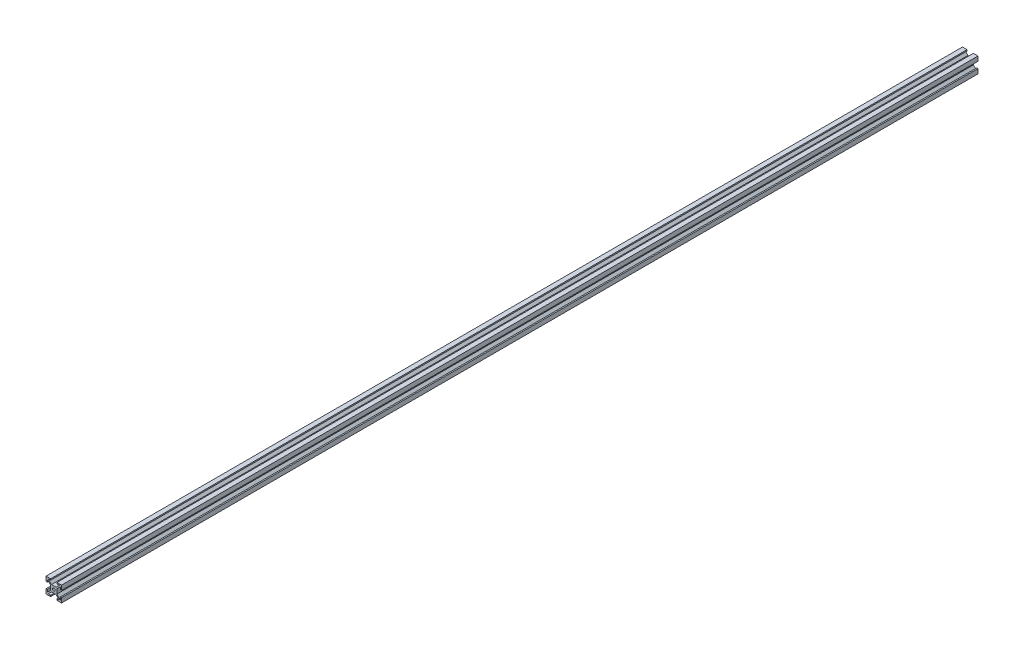
SolidWorks part; units mm, degrees
ref_plane "Front Plane" through (0, 0, 0) normal (0, 0, 1) x (1, 0, 0)
ref_plane "Top Plane" through (0, 0, 0) normal (0, 1, 0) x (1, 0, 0)
ref_plane "Right Plane" through (0, 0, 0) normal (1, 0, 0) x (0, 0, -1)
sketch "Sketch1" plane through (0, 0, 0) normal (0, 0, 1) x (1, 0, 0)
  line L0 (-8.38, 4.1) -> (-10, 4.1)
  line L1 (-2.9545, 4.1) -> (2.9545, 4.1)
  line L2 (-4.1, 2.9545) -> (-4.1, -2.9545)
  line L3 (-2.9545, -4.1) -> (2.9545, -4.1)
  line L4 (4.1, 2.9545) -> (4.1, -2.9545)
  line L5 (-4.1, 4.1) -> (4.1, -4.1) construction
  line L6 (-4.1, -4.1) -> (4.1, 4.1) construction
  line L7 (-10, 10) -> (-4.1, 10)
  line L8 (-10, 10) -> (-10, 4.1)
  line L9 (-10, -10) -> (-4.1, -10)
  line L10 (10, 10) -> (10, 4.1)
  line L11 (-10, 10) -> (10, -10) construction
  line L12 (-10, -10) -> (10, 10) construction
  line L13 (-7.2345, 8.38) -> (-4.1, 8.38)
  line L14 (-8.38, 7.2345) -> (-8.38, 4.1)
  line L15 (-7.2345, -8.38) -> (-4.1, -8.38)
  line L16 (8.38, 7.2345) -> (8.38, 4.1)
  line L17 (-8.38, 8.38) -> (8.38, -8.38) construction
  line L18 (-8.38, -8.38) -> (8.38, 8.38) construction
  line L19 (-4.1, 8.38) -> (-4.1, 10)
  line L20 (4.1, 10) -> (4.1, 8.38)
  line L21 (8.38, 4.1) -> (10, 4.1)
  line L22 (-8.38, -4.1) -> (-10, -4.1)
  line L23 (-4.1, -8.38) -> (-4.1, -10)
  line L24 (8.38, -4.1) -> (10, -4.1)
  line L25 (4.1, -8.38) -> (4.1, -10)
  line L26 (-5.464, 5.464) -> (-4.8912, 6.0368) construction
  line L27 (-4.1, 2.9545) -> (-8.38, 7.2345)
  line L28 (-2.9545, 4.1) -> (-7.2345, 8.38)
  line L29 (0, 11.3108) -> (0, -17.1823) construction
  line L30 (-16.7028, 0) -> (14.4032, 0) construction
  line L31 (-2.9545, -4.1) -> (-7.2345, -8.38)
  line L32 (-4.1, -2.9545) -> (-8.38, -7.2345)
  line L33 (2.9545, -4.1) -> (7.2345, -8.38)
  line L34 (4.1, -2.9545) -> (8.38, -7.2345)
  line L35 (4.1, 2.9545) -> (8.38, 7.2345)
  line L36 (2.9545, 4.1) -> (7.2345, 8.38)
  line L37 (4.1, 8.38) -> (7.2345, 8.38)
  line L38 (4.1, 10) -> (10, 10)
  line L39 (-8.38, -4.1) -> (-8.38, -7.2345)
  line L40 (-10, -4.1) -> (-10, -10)
  line L41 (8.38, -4.1) -> (8.38, -7.2345)
  line L42 (10, -4.1) -> (10, -10)
  line L43 (4.1, -8.38) -> (7.2345, -8.38)
  line L44 (4.1, -10) -> (10, -10)
  circle A0 centre (0, 0) radius 1.77
  point P0 (0, 0)
  point P6 (0, 0)
  dimension "D5" = 3.54
  dimension "D1" = 8.2
  dimension "D2" = 20
  dimension "D3" = 8.2
  dimension "D4" = 20
  dimension "D6" = 16.76
  dimension "D7" = 16.76
  dimension "D8" = 0.81
  dimension "D9" = 135
  dimension "D10" = 7.7696
  dimension "D11" = 5.0536
extrude "Boss-Extrude1" add sketch "Sketch1" along normal blind 1180
